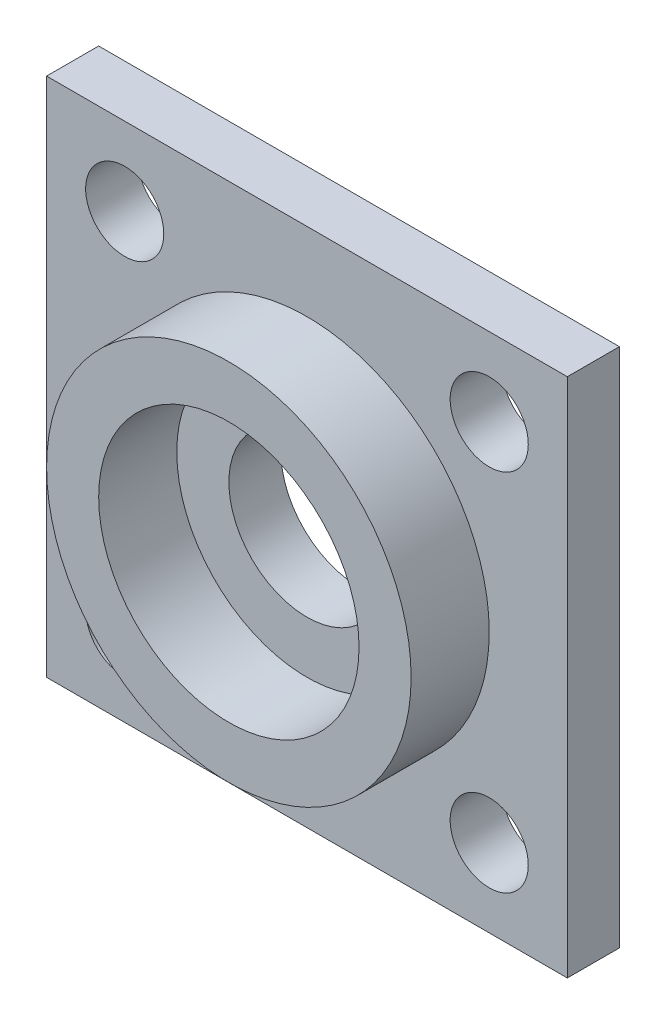
SolidWorks part; units mm, degrees
ref_plane "前视基准面" through (0, 0, 0) normal (0, 0, 1) x (1, 0, 0)
ref_plane "上视基准面" through (0, 0, 0) normal (0, 1, 0) x (1, 0, 0)
ref_plane "右视基准面" through (0, 0, 0) normal (1, 0, 0) x (0, 0, -1)
other "Configuration Table"
sketch "草图1" plane through (0, 0, 0) normal (0, 0, 1) x (1, 0, 0)
  line L1 (-10, 10) -> (10, 10)
  line L2 (-10, 10) -> (-10, -10)
  line L3 (-10, -10) -> (10, -10)
  line L4 (10, 10) -> (10, -10)
  line L5 (-10, 10) -> (10, -10) construction
  line L6 (-10, -10) -> (10, 10) construction
  circle A0 centre (-7, 7) radius 1.5
  circle A1 centre (7, 7) radius 1.5
  circle A2 centre (7, -7) radius 1.5
  circle A3 centre (-7, -7) radius 1.5
  circle A4 centre (0, 0) radius 3
  point P0 (0, 0)
  point P17 (0, 0)
  dimension "D3" = 3
  dimension "D1" = 20
  dimension "D2" = 20
  dimension "D4" = 4
extrude "凸台-拉伸1" add sketch "草图1" along normal blind 2
sketch "草图2" plane through (0, 0, 2) normal (0, 0, 1) x (1, 0, 0)
  circle A0 centre (0, 0) radius 5
  circle A1 centre (0, 0) radius 7
extrude "凸台-拉伸2" add sketch "草图2" along normal blind 3
